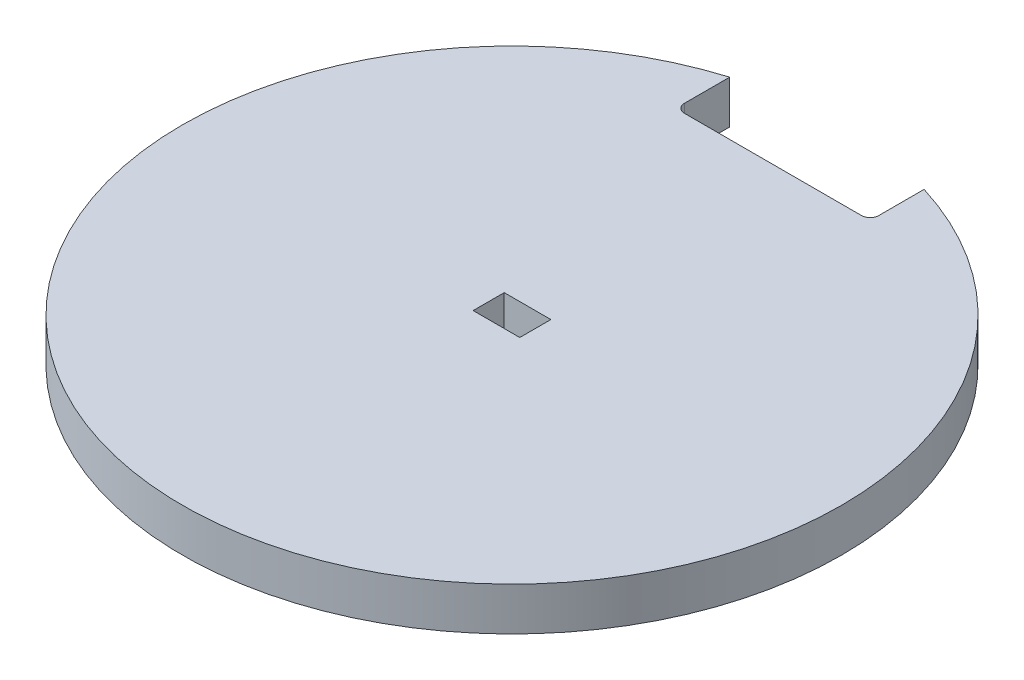
SolidWorks part; units mm, degrees
ref_plane "Front Plane" through (0, 0, 0) normal (0, 0, 1) x (1, 0, 0)
ref_plane "Top Plane" through (0, 0, 0) normal (0, 1, 0) x (1, 0, 0)
ref_plane "Right Plane" through (0, 0, 0) normal (1, 0, 0) x (0, 0, -1)
sketch "Sketch1" plane through (0, 0, 0) normal (0, 1, 0) x (1, 0, 0)
  line L0 (7.1456, 36.4503) -> (7.1456, 30.8969)
  line L1 (-15.3544, 36.4503) -> (-15.3544, 31.2026)
  line L2 (-14.3544, 30.2026) -> (6.1456, 30.2026)
  line L3 (-6.8044, -1.8) -> (-1.4044, -1.8)
  line L8 (-6.8044, -1.8) -> (-6.8044, 1.8)
  line L9 (-6.8044, 1.8) -> (-1.4044, 1.8)
  line L10 (-1.4044, -1.8) -> (-1.4044, 1.8)
  line L11 (-6.8044, -1.8) -> (-1.4044, 1.8) construction
  line L12 (-6.8044, 1.8) -> (-1.4044, -1.8) construction
  arc A0 (-15.3544, 31.2026) -> (-14.3544, 30.2026) centre (-14.3544, 31.2026) ccw
  arc A1 (6.1456, 30.2026) -> (7.1456, 31.2026) centre (6.1456, 31.2026) ccw
  circle A3 centre (-4.1044, 0) radius 38.1469
  dimension "D1" = 3.6
  dimension "D2" = 5.4
extrude "Boss-Extrude1" add sketch "Sketch1" along normal blind 5
